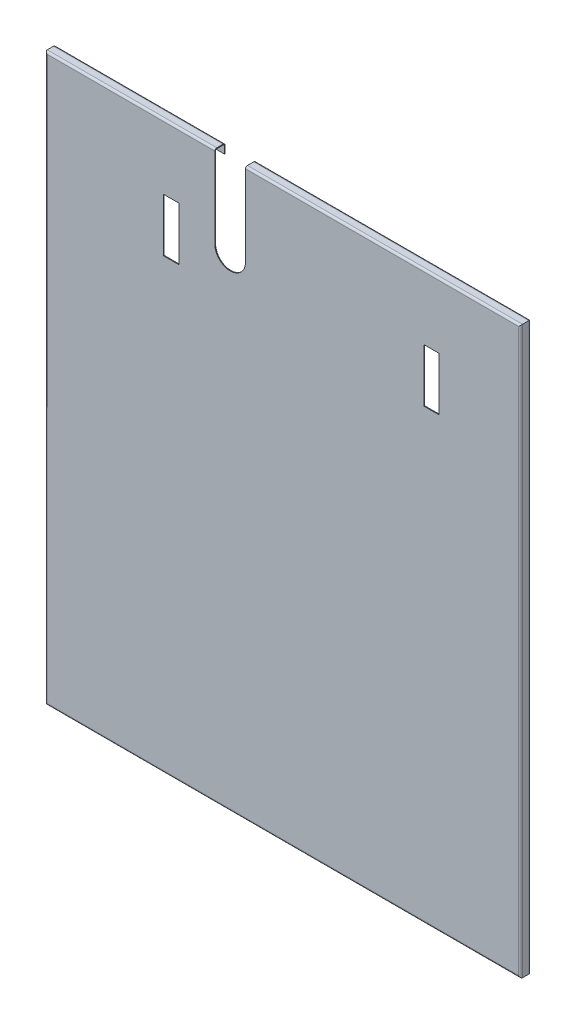
SolidWorks part; units mm, degrees
ref_plane "정면" through (0, 0, 0) normal (0, 0, 1) x (1, 0, 0)
ref_plane "윗면" through (0, 0, 0) normal (0, 1, 0) x (1, 0, 0)
ref_plane "우측면" through (0, 0, 0) normal (1, 0, 0) x (0, 0, -1)
sketch "스케치1" plane through (0, 0, 0) normal (0, 0, 1) x (1, 0, 0)
  line L1 (0, 0) -> (776, 0)
  line L2 (0, 0) -> (0, 924)
  line L3 (0, 924) -> (776, 924)
  line L4 (776, 0) -> (776, 924)
  line L5 (193, 818) -> (218, 818)
  line L6 (193, 818) -> (193, 731)
  line L7 (193, 731) -> (218, 731)
  line L8 (218, 818) -> (218, 731)
  line L9 (618, 818) -> (643, 818)
  line L10 (618, 818) -> (618, 731)
  line L11 (618, 731) -> (643, 731)
  line L12 (643, 818) -> (643, 731)
  point P14 (218, 774.5)
  dimension "D1" = 924
  dimension "D2" = 776
  dimension "D3" = 193
  dimension "D4" = 25
  dimension "D5" = 400
  dimension "D6" = 25
  dimension "D7" = 87
  dimension "D8" = 731
extrude "보스-돌출1" add sketch "스케치1" along normal blind 1.2
sketch "스케치2" plane through (0, 0, 0) normal (0, 0, -1) x (-1, 0, 0)
  line L0 (-1.2, 922.8) -> (-774.8, 922.8)
  line L1 (-774.8, 922.8) -> (-774.8, 1.2)
  line L2 (-774.8, 1.2) -> (-1.2, 1.2)
  line L3 (-1.2, 1.2) -> (-1.2, 922.8)
  line L4 (0, 0) -> (0, 924)
  line L5 (0, 924) -> (-776, 924)
  line L6 (-776, 924) -> (-776, 0)
  line L7 (-776, 0) -> (0, 0)
  line L8 (0, 0) -> (0, 924)
  line L9 (0, 924) -> (-776, 924)
  line L10 (-776, 924) -> (-776, 0)
  line L11 (-776, 0) -> (0, 0)
  dimension "D1" = 0
  dimension "D2" = 1.2
extrude "보스-돌출2" add sketch "스케치2" along normal blind 15.5
sketch "스케치3" plane through (0, 0, -15.5) normal (0, 0, -1) x (-1, 0, 0)
  line L0 (-15, 909) -> (-761, 909)
  line L1 (-761, 909) -> (-761, 15)
  line L2 (-761, 15) -> (-15, 15)
  line L3 (-15, 15) -> (-15, 909)
  line L4 (-776, 0) -> (0, 0)
  line L5 (0, 0) -> (0, 924)
  line L6 (0, 924) -> (-776, 924)
  line L7 (-776, 924) -> (-776, 0)
  line L8 (-776, 0) -> (0, 0)
  line L9 (0, 0) -> (0, 924)
  line L10 (0, 924) -> (-776, 924)
  line L11 (-776, 924) -> (-776, 0)
  dimension "D1" = 0
  dimension "D2" = 15
extrude "보스-돌출3" add sketch "스케치3" against normal blind 1.2
fillet "필렛1" radius 2 12 edges at (774.8, 462, 0) (774.8, 462, -14.3) (388, 1.2, 0) (388, 1.2, -14.3) (774.8, 1.2, -7.15) (1.2, 462, 0) (1.2, 462, -14.3) (1.2, 1.2, -7.15) (388, 922.8, 0) (774.8, 922.8, -7.15) (388, 922.8, -14.3) (1.2, 922.8, -7.15)
fillet "필렛2" radius 3.2 4 edges at (388, 924, 1.2) (388, 0, 1.2) (0, 462, 1.2) (776, 462, 1.2)
fillet "필렛3" radius 3.2 4 edges at (776, 462, -15.5) (388, 924, -15.5) (0, 462, -15.5) (388, 0, -15.5)
sketch "스케치4" plane through (0, 0, 1.2) normal (0, 0, 1) x (1, 0, 0)
  line L0 (302, 982.2572) -> (302, 789) construction
  line L1 (327, 982.2572) -> (327, 789)
  line L2 (277, 982.2572) -> (277, 789)
  line L3 (0, 924) -> (776, 924) construction
  line L5 (0, 0) -> (0, 924) construction
  arc A0 (327, 982.2572) -> (277, 982.2572) centre (302, 982.2572) ccw
  arc A1 (277, 789) -> (327, 789) centre (302, 789) ccw
  point P2 (302, 885.6286)
  dimension "D1" = 25
  dimension "D2" = 135
  dimension "D3" = 277
extrude "컷-돌출1" cut sketch "스케치4" against normal through all
